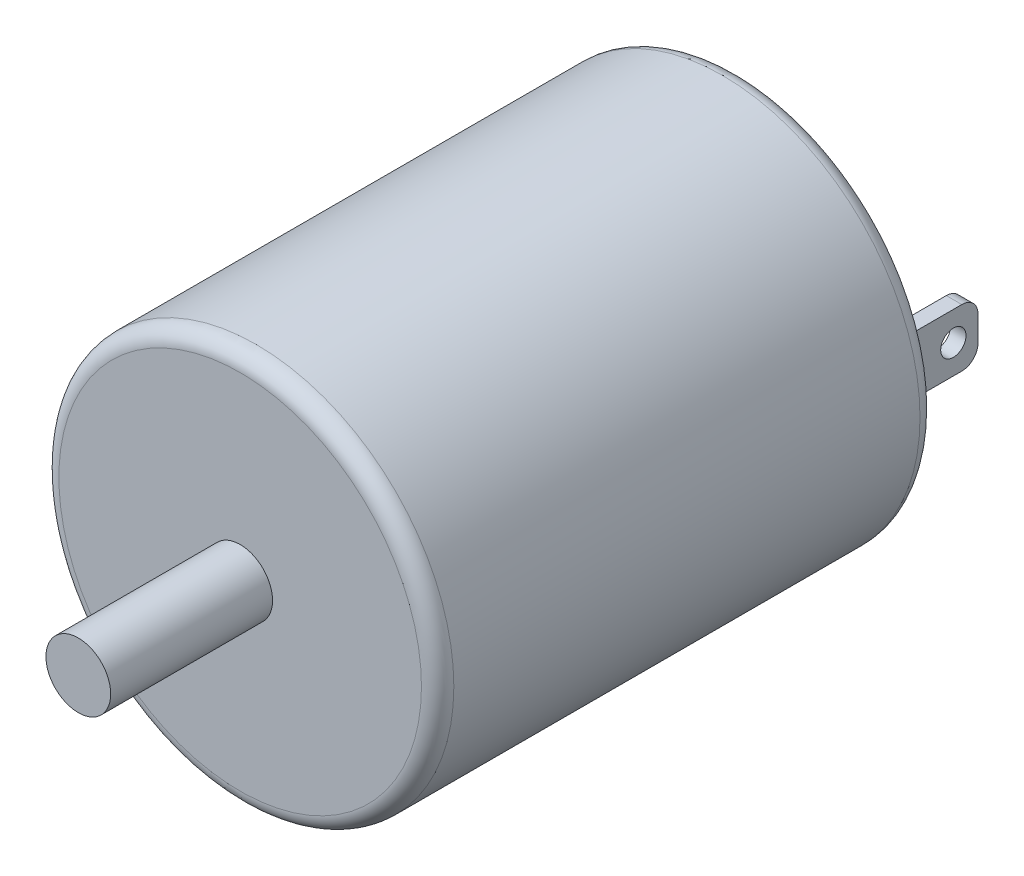
SolidWorks part; units mm, degrees
material "201.0-T43 Molde de fundição com isolamento (SS)"
ref_plane "Plano frontal" through (0, 0, 0) normal (0, 0, 1) x (1, 0, 0)
ref_plane "Plano superior" through (0, 0, 0) normal (0, 1, 0) x (1, 0, 0)
ref_plane "Plano direito" through (0, 0, 0) normal (1, 0, 0) x (0, 0, -1)
sketch "Esboço1" plane through (0, 0, 0) normal (0, 0, 1) x (1, 0, 0)
  circle A0 centre (0, 0) radius 12.2
  dimension "D1" = 24.4
extrude "Ressalto-extrusão1" add sketch "Esboço1" along normal blind 30.8
fillet "Filete1" radius 1 2 edges at (12.2, 0, 0) (12.2, 0, 30.8)
sketch "Esboço2" plane through (0, 0, 30.8) normal (0, 0, 1) x (1, 0, 0)
  circle A0 centre (0, 0) radius 2
  dimension "D1" = 4
extrude "Ressalto-extrusão2" add sketch "Esboço2" along normal blind 10
sketch "Esboço4" plane through (0, 0, 0) normal (0, 0, -1) x (-1, 0, 0)
  line L1 (-9.7828, 2.3302) -> (-8.8239, 2.3302)
  line L2 (-9.7828, 2.3302) -> (-9.7828, -1.234)
  line L3 (-9.7828, -1.234) -> (-8.8239, -1.234)
  line L4 (-8.8239, 2.3302) -> (-8.8239, -1.234)
  line L5 (8.817, 2.3302) -> (7.9226, 2.3302)
  line L6 (8.817, 2.3302) -> (8.817, -1.234)
  line L7 (8.817, -1.234) -> (7.9226, -1.234)
  line L8 (7.9226, 2.3302) -> (7.9226, -1.234)
extrude "Ressalto-extrusão3" add sketch "Esboço4" along normal blind 5
fillet "Filete2" radius 1 4 edges at (-8.3698, 2.3302, -5) (-8.3698, -1.234, -5) (9.3034, 2.3302, -5) (9.3034, -1.234, -5)
sketch "Esboço5" plane through (9.7828, 0, 0) normal (1, 0, 0) x (0, 0, -1)
  circle A0 centre (3.4772, 0.5481) radius 0.7821
extrude "Corte-extrusão2" cut sketch "Esboço5" against normal through all
